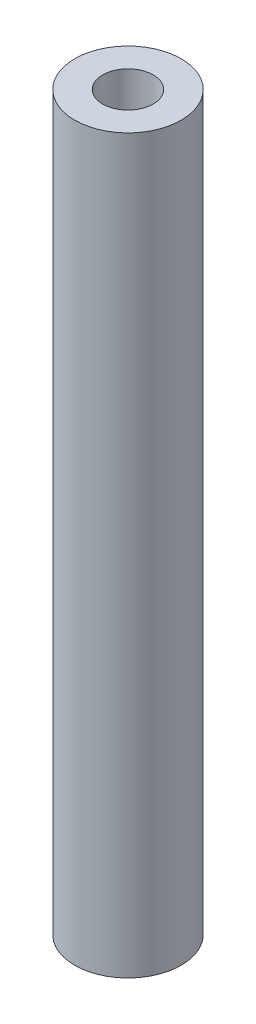
SolidWorks part; units mm, degrees
ref_plane "前视基准面" through (0, 0, 0) normal (0, 0, 1) x (1, 0, 0)
ref_plane "上视基准面" through (0, 0, 0) normal (0, 1, 0) x (1, 0, 0)
ref_plane "右视基准面" through (0, 0, 0) normal (1, 0, 0) x (0, 0, -1)
other "Configuration Table"
sketch "草图1" plane through (0, 0, 0) normal (0, 1, 0) x (1, 0, 0)
  circle A0 centre (0, 0) radius 1.9
  circle A1 centre (0, 0) radius 4
  dimension "D1" = 3.8
  dimension "D2" = 8
extrude "凸台-拉伸1" add sketch "草图1" along normal blind 55
